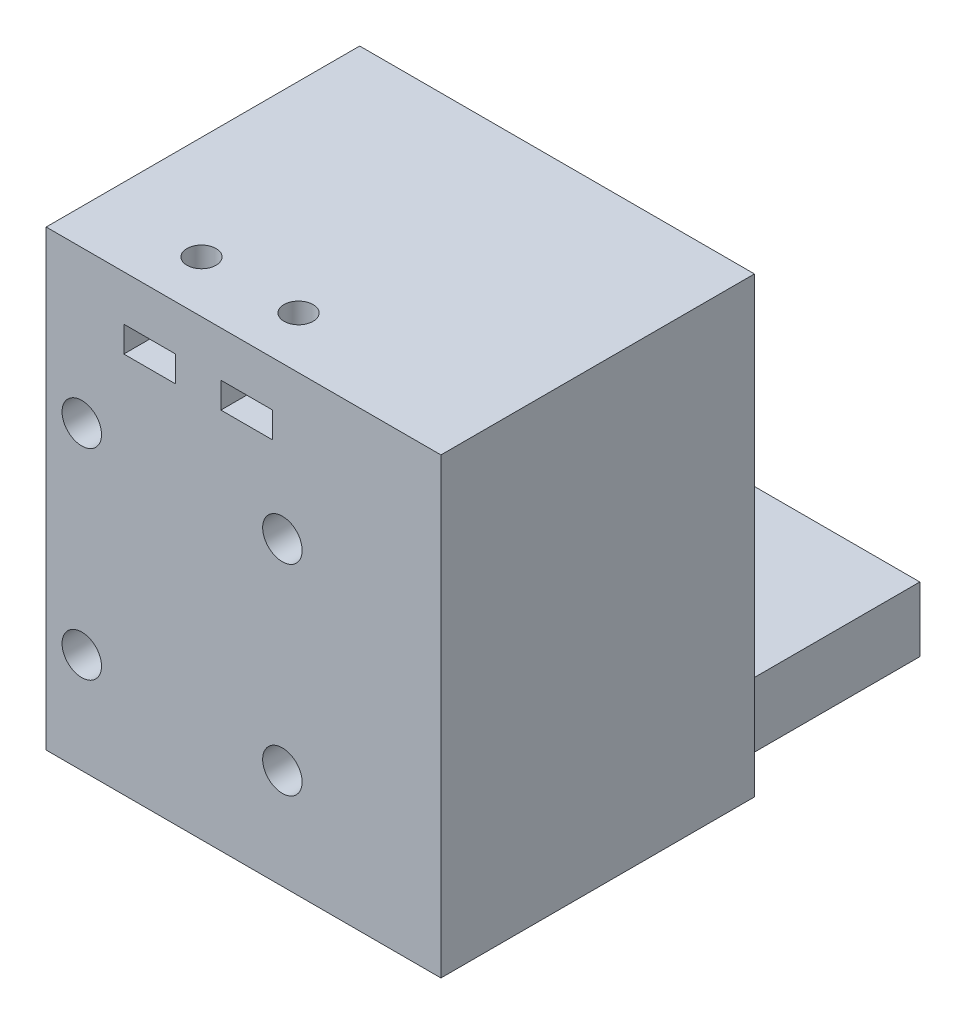
SolidWorks part; units mm, degrees
ref_plane "Front Plane" through (0, 0, 0) normal (0, 0, 1) x (1, 0, 0)
ref_plane "Top Plane" through (0, 0, 0) normal (0, 1, 0) x (1, 0, 0)
ref_plane "Right Plane" through (0, 0, 0) normal (1, 0, 0) x (0, 0, -1)
sketch "Sketch1" plane through (0, 0, 0) normal (0, 0, 1) x (1, 0, 0)
  line L0 (21, 42) -> (21, 32.8057) construction
  line L1 (0, 0) -> (42, 0)
  line L2 (0, 0) -> (0, 42)
  line L3 (0, 42) -> (42, 42)
  line L4 (42, 0) -> (42, 42)
  line L5 (0, 21) -> (7.8682, 21) construction
  circle A0 centre (21, 21) radius 11.5
  circle A1 centre (5.5, 36.5) radius 1.7
  circle A2 centre (36.5, 36.5) radius 1.7
  circle A3 centre (5.5, 5.5) radius 1.7
  circle A4 centre (36.5, 5.5) radius 1.7
  dimension "D3" = 3.4
  dimension "D8" = 23
  dimension "D1" = 42
  dimension "D2" = 42
  dimension "D4" = 31
  dimension "D5" = 15.5
  dimension "D6" = 31
  dimension "D7" = 15.5
extrude "Boss-Extrude1" add sketch "Sketch1" along normal blind 3
sketch "Sketch2" plane through (0, 0, 0) normal (0, -1, 0) x (-1, 0, 0)
  line L0 (0, -48.445) -> (0, 31.555)
  line L1 (0, 47.85) -> (0, 0) construction
  line L2 (0, 31.555) -> (-55, 31.555)
  line L4 (-55, 31.555) -> (-55, -48.445)
  line L5 (-55, -48.445) -> (0, -48.445)
  line L6 (5, -48.445) -> (-30, -48.445) construction
  line L7 (0, -3) -> (0, 0) construction
  line L8 (-27.5, -48.445) -> (-27.5, -26.7606) construction
  line L9 (-42, -3) -> (0, -3) construction
  line L10 (-37, -3) -> (-5, -3)
  line L11 (-37, -3) -> (-37, -26)
  line L12 (-37, -26) -> (-5, -26)
  line L13 (-5, -3) -> (-5, -26)
  line L14 (-21, -3) -> (-21, -19.9784) construction
  line L16 (0, -3) -> (-42, -3) construction
  circle A0 centre (-40, 22.555) radius 4.05
  circle A1 centre (-40, -39.445) radius 4.05
  dimension "D2" = 8.1
  dimension "D1" = 80
  dimension "D3" = 55
  dimension "D4" = 9
  dimension "D5" = 19
  dimension "D6" = 5
  dimension "D7" = 23
  dimension "D8" = 9
extrude "Boss-Extrude2" add sketch "Sketch2" along normal blind 10
sketch "Sketch3" plane through (0, 0, 3) normal (0, 0, 1) x (1, 0, 0)
  line L0 (0, 21) -> (9.5, 21)
  line L1 (0, 42) -> (0, 0) construction
  line L2 (32.5, 21) -> (42, 21)
  line L3 (42, 0) -> (42, 42) construction
  line L4 (42, 21) -> (42, 42)
  line L5 (42, 42) -> (0, 42)
  line L6 (0, 42) -> (0, 21)
  circle A0 centre (21, 21) radius 11.5 construction
  arc A1 (32.5, 21) -> (9.5, 21) centre (21, 21) ccw
extrude "Boss-Extrude3" add sketch "Sketch3" along normal up to surface (23 mm away) up to face at (21, -5, 26)
sketch "Sketch4" plane through (0, 0, 0) normal (0, 1, 0) x (1, 0, 0)
  circle A0 centre (40, 22.555) radius 4.05 construction
  circle A1 centre (40, -39.445) radius 4.05 construction
  circle A2 centre (40, 22.555) radius 4.05
  circle A3 centre (40, -39.445) radius 4.05
extrude "Boss-Extrude4" add sketch "Sketch4" against normal blind 3
sketch "Sketch5" plane through (0, 0, 0) normal (0, 1, 0) x (1, 0, 0)
  line L1 (42, -26) -> (0, -26)
  line L2 (42, -26) -> (42, -48.445)
  line L3 (42, -48.445) -> (0, -48.445)
  line L4 (0, -26) -> (0, -48.445)
extrude "Boss-Extrude5" add sketch "Sketch5" along normal up to surface (42 mm away) up to face at (21, 42, 13)
sketch "Sketch6" plane through (0, 0, 0) normal (0, 0, -1) x (-1, 0, 0)
  circle A0 centre (-5.5, 36.5) radius 1.7 construction
  circle A1 centre (-5.5, 36.5) radius 1.7
  circle A2 centre (-36.5, 36.5) radius 1.7 construction
  circle A3 centre (-36.5, 36.5) radius 1.7
extrude "Cut-Extrude1" cut sketch "Sketch6" against normal through all
sketch "Sketch7" plane through (0, 0, 48.445) normal (0, 0, 1) x (1, 0, 0)
  circle A0 centre (5.5, 36.5) radius 3.05
  circle A1 centre (36.5, 36.5) radius 3.05
  circle A2 centre (5.5, 5.5) radius 3.05
  circle A3 centre (36.5, 5.5) radius 3.05
  circle A4 centre (36.5, 5.5) radius 1.7 construction
  circle A5 centre (5.5, 5.5) radius 1.7 construction
  dimension "D1" = 6.1
extrude "Cut-Extrude2" cut sketch "Sketch7" against normal offset from surface (43.445 mm away) 5 up to face at (7.2, 5.5, 0)
sketch "Sketch8" plane through (0, 0, 48.445) normal (0, 0, 1) x (1, 0, 0)
  line L0 (55, -10) -> (61, -10)
  line L2 (61, -10) -> (61, 60)
  line L3 (61, 60) -> (0, 60)
  line L4 (0, 60) -> (0, 42)
  line L6 (55, -10) -> (55, 0) construction
  line L7 (55, 0) -> (42, 0) construction
  line L8 (42, 42) -> (42, 0) construction
  line L9 (42, 42) -> (0, 42) construction
  line L10 (55, -10) -> (55, 0)
  line L11 (55, 0) -> (42, 0)
  line L12 (42, 42) -> (42, 0)
  line L13 (42, 42) -> (0, 42)
  dimension "D1" = 6
  dimension "D2" = 70
extrude "Boss-Extrude6" add sketch "Sketch8" against normal up to surface (48.445 mm away) up to face at (7.2, 5.5, 0)
sketch "Sketch9" plane through (0, 0, 0) normal (0, 0, -1) x (-1, 0, 0)
  line L0 (-61, 60) -> (0, 60) construction
  circle A0 centre (-48.5, 52.5) radius 2
  circle A1 centre (-48.5, 37.5) radius 2
  dimension "D4" = 4
  dimension "D1" = 15
  dimension "D2" = 7.5
  dimension "D3" = 12.5
extrude "Cut-Extrude3" cut sketch "Sketch9" against normal blind 5
ref_plane "Plane1" through (25.6, 0, 0) normal (-1, 0, 0) x (0, 0, 1)
ref_plane "Plane2" through (0, 10, 0) normal (0, -1, 0) x (-1, 0, 0)
sketch "Sketch10" plane through (0, 60, 0) normal (0, 1, 0) x (1, 0, 0)
  circle A0 centre (31, -40.445) radius 2.25
  circle A1 centre (16, -40.445) radius 2.25
  dimension "D3" = 4.5
  dimension "D1" = 8
  dimension "D2" = 30
  dimension "D4" = 15
extrude "Cut-Extrude4" cut sketch "Sketch10" against normal blind 15
sketch "Sketch11" plane through (0, 0, 48.445) normal (0, 0, 1) x (1, 0, 0)
  line L0 (61, 60) -> (0, 60) construction
  line L1 (12, 53) -> (20, 53)
  line L2 (12, 53) -> (12, 49)
  line L3 (12, 49) -> (20, 49)
  line L4 (20, 53) -> (20, 49)
  line L5 (27, 53) -> (35, 53)
  line L6 (27, 53) -> (27, 49)
  line L7 (27, 49) -> (35, 49)
  line L8 (35, 53) -> (35, 49)
  line L9 (16, 60) -> (16, 38.3031) construction
  line L10 (31, 60) -> (31, 36.3857) construction
  line L11 (31, 45) -> (31, 60) construction
  line L12 (16, 45) -> (16, 60) construction
  point P18 (31, 53)
  point P19 (16, 53)
  dimension "D1" = 7
  dimension "D2" = 4
  dimension "D3" = 8
extrude "Cut-Extrude5" cut sketch "Sketch11" against normal blind 13
sketch "Sketch12" plane through (0, 0, 0) normal (-1, 0, 0) x (0, 0, 1)
  line L0 (14.5, 21) -> (14.5, 60) construction
  line L1 (26, 21) -> (3, 21) construction
  line L2 (0, 60) -> (48.445, 60) construction
  text T0 "B" font "Century Gothic" height 10
extrude "Cut-Extrude6" cut sketch "Sketch12" against normal blind 0.5
